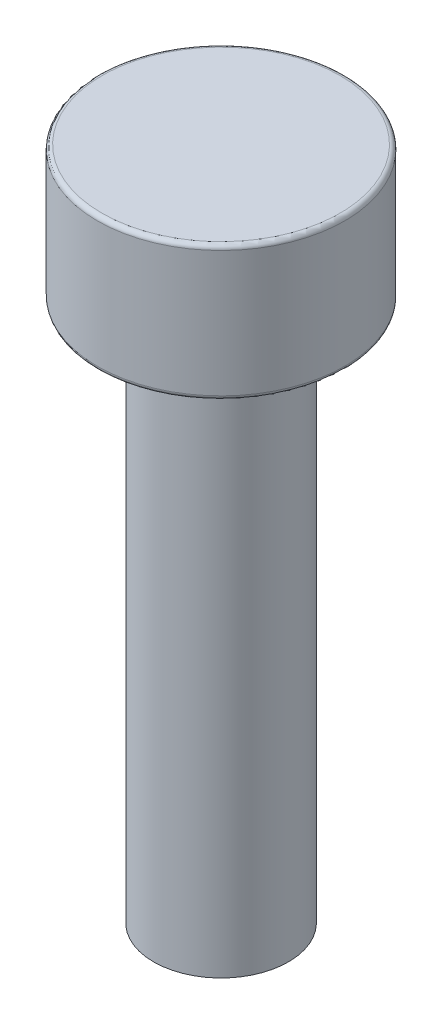
SolidWorks part; units mm, degrees
ref_plane "Front Plane" through (0, 0, 0) normal (0, 0, 1) x (1, 0, 0)
ref_plane "Top Plane" through (0, 0, 0) normal (0, 1, 0) x (1, 0, 0)
ref_plane "Right Plane" through (0, 0, 0) normal (1, 0, 0) x (0, 0, -1)
sketch "Sketch1" plane through (0, 0, 0) normal (0, 1, 0) x (1, 0, 0)
  circle A0 centre (0, 0) radius 1.5
  dimension "D1" = 3
extrude "Boss-Extrude1" add sketch "Sketch1" along normal blind 12
sketch "Sketch2" plane through (0, 12, 0) normal (0, 1, 0) x (1, 0, 0)
  circle A0 centre (0, 0) radius 2.75
  dimension "D1" = 5.5
extrude "Boss-Extrude2" add sketch "Sketch2" along normal blind 3
fillet "Fillet1" radius 0.2 1 edges at (0, 12, 1.5)
fillet "Fillet2" radius 0.1 1 edges at (0, 15, 2.75)
fillet "Fillet3" radius 0.1 1 edges at (0, 12, 2.75)
